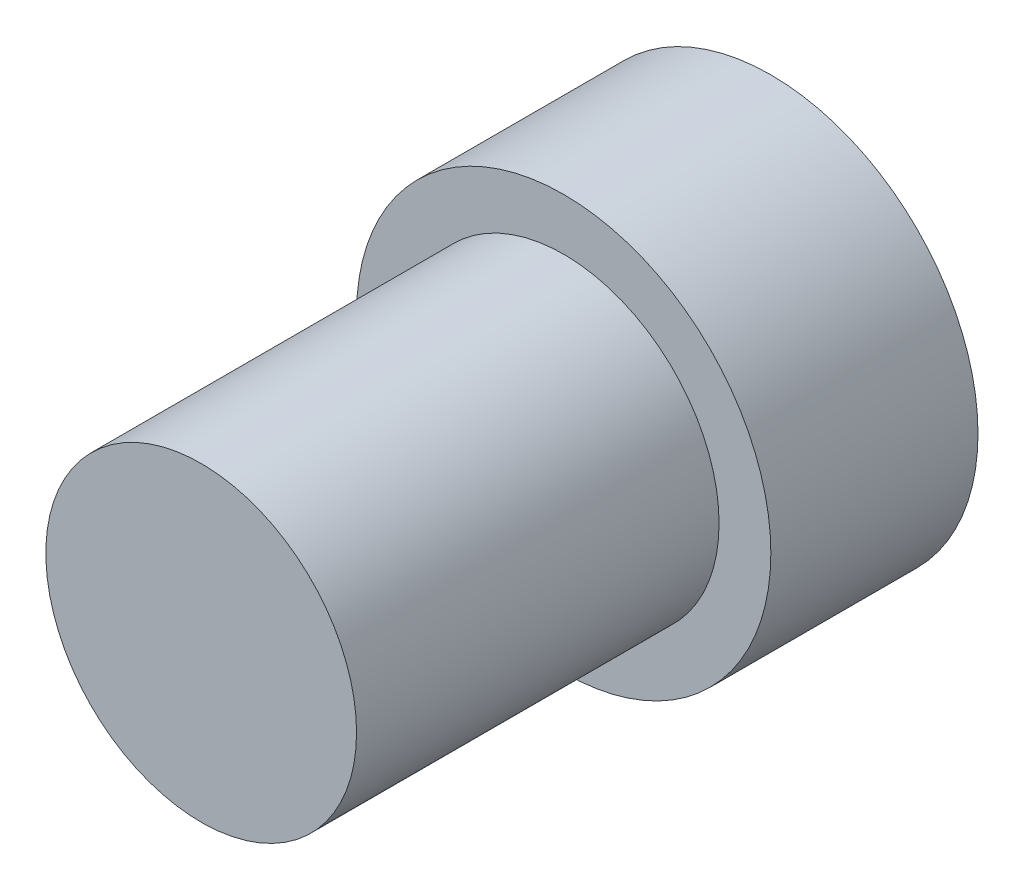
SolidWorks part; units mm, degrees
ref_plane "Front Plane" through (0, 0, 0) normal (0, 0, 1) x (1, 0, 0)
ref_plane "Top Plane" through (0, 0, 0) normal (0, 1, 0) x (1, 0, 0)
ref_plane "Right Plane" through (0, 0, 0) normal (1, 0, 0) x (0, 0, -1)
sketch "Sketch1" plane through (0, 0, 0) normal (0, 0, 1) x (1, 0, 0)
  circle A0 centre (0, 0) radius 4
  dimension "D1" = 8
extrude "Boss-Extrude1" add sketch "Sketch1" along normal blind 4
sketch "Sketch3" plane through (0, 0, 4) normal (0, 0, 1) x (1, 0, 0)
  circle A0 centre (0, 0) radius 3
  dimension "D1" = 6
extrude "Boss-Extrude2" add sketch "Sketch3" along normal blind 7
